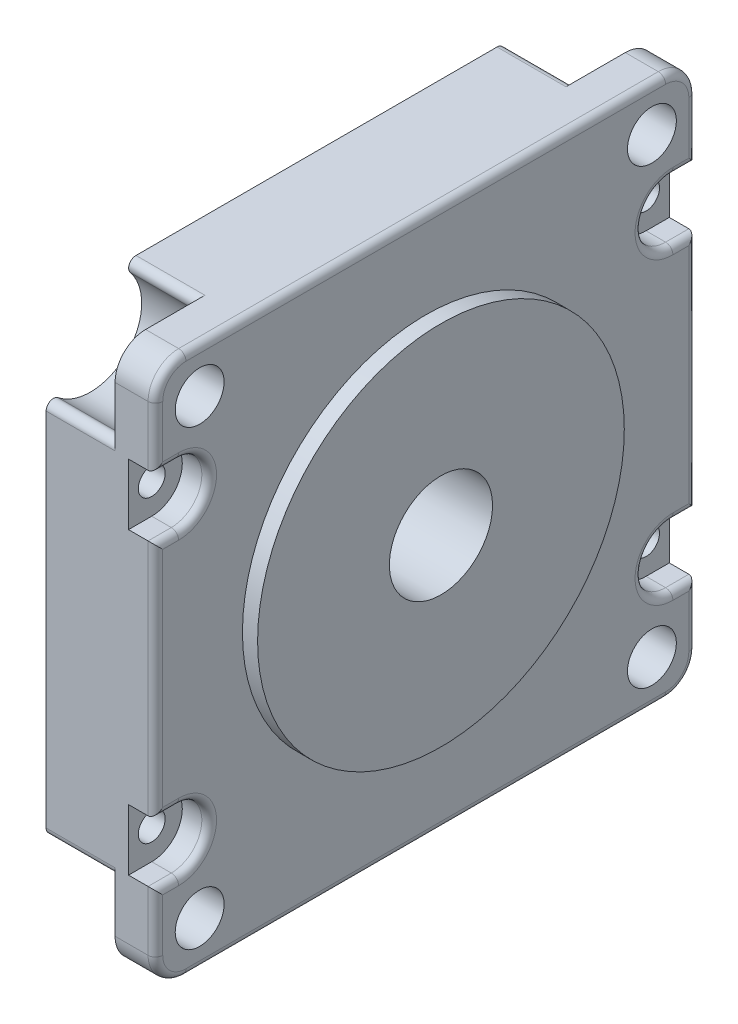
SolidWorks part; units mm, degrees
material "6061-T6 (SS)"
ref_plane "Front Plane" through (0, 0, 0) normal (0, 0, 1) x (1, 0, 0)
ref_plane "Top Plane" through (0, 0, 0) normal (0, 1, 0) x (1, 0, 0)
ref_plane "Right Plane" through (0, 0, 0) normal (1, 0, 0) x (0, 0, -1)
sketch "Sketch1" plane through (0, 0, 0) normal (1, 0, 0) x (0, 0, -1)
  line L1 (-28.0924, -28.0924) -> (28.0924, -28.0924)
  line L2 (-28.0924, -28.0924) -> (-28.0924, 28.0924)
  line L3 (-28.0924, 28.0924) -> (28.0924, 28.0924)
  line L4 (28.0924, -28.0924) -> (28.0924, 28.0924)
  line L5 (-28.0924, -28.0924) -> (28.0924, 28.0924) construction
  line L6 (-28.0924, 28.0924) -> (28.0924, -28.0924) construction
  point P0 (0, 0)
  dimension "D1" = 56.1848
  dimension "D2" = 56.1848
extrude "Boss-Extrude1" add sketch "Sketch1" along normal blind 11.3538
sketch "Sketch2" plane through (11.3538, 0, 0) normal (1, 0, 0) x (0, 0, -1)
  line L0 (0, 28.0924) -> (0, 0) construction
  line L1 (28.0924, 28.0924) -> (-28.0924, 28.0924) construction
  line L2 (0, 0) -> (-28.0924, 0) construction
  line L3 (-28.0924, 28.0924) -> (-28.0924, -28.0924) construction
  circle A0 centre (-23.495, 23.495) radius 2.54
  circle A1 centre (23.495, 23.495) radius 2.54
  circle A2 centre (23.495, -23.495) radius 2.54
  circle A3 centre (-23.495, -23.495) radius 2.54
  dimension "D1" = 5.08
  dimension "D2" = 46.99
  dimension "D3" = 46.99
extrude "Cut-Extrude1" cut sketch "Sketch2" against normal through all
sketch "Sketch3" plane through (11.3538, 0, 0) normal (1, 0, 0) x (0, 0, -1)
  line L0 (0, 28.0924) -> (0, 0) construction
  line L1 (28.0924, 28.0924) -> (-28.0924, 28.0924) construction
  line L2 (0, 0) -> (-28.0924, 0) construction
  line L3 (-28.0924, 28.0924) -> (-28.0924, -28.0924) construction
  line L4 (-25.6794, 15.5443) -> (-22.5044, 15.5443) construction
  line L5 (-22.5044, 15.5443) -> (-22.5044, 20.6548) construction
  line L6 (-25.6794, 18.7193) -> (-28.0924, 18.7193)
  line L7 (-25.6794, 12.3693) -> (-28.0924, 12.3693)
  line L8 (-28.0924, 18.7193) -> (-28.0924, 12.3693)
  line L9 (-28.0924, -18.7193) -> (-28.0924, -12.3693)
  line L10 (28.0924, 18.7193) -> (28.0924, 12.3693)
  line L11 (25.6794, 12.3693) -> (28.0924, 12.3693)
  line L12 (25.6794, 18.7193) -> (28.0924, 18.7193)
  line L13 (-25.6794, -12.3693) -> (-28.0924, -12.3693)
  line L14 (-25.6794, -18.7193) -> (-28.0924, -18.7193)
  line L15 (25.6794, -18.7193) -> (28.0924, -18.7193)
  line L16 (25.6794, -12.3693) -> (28.0924, -12.3693)
  line L17 (28.0924, -18.7193) -> (28.0924, -12.3693)
  arc A0 (-25.6794, 12.3693) -> (-25.6794, 18.7193) centre (-25.6794, 15.5443) ccw
  arc A1 (25.6794, 12.3693) -> (25.6794, 18.7193) centre (25.6794, 15.5443) cw
  arc A2 (-25.6794, -12.3693) -> (-25.6794, -18.7193) centre (-25.6794, -15.5443) cw
  arc A3 (25.6794, -12.3693) -> (25.6794, -18.7193) centre (25.6794, -15.5443) ccw
  dimension "D2" = 3.175
  dimension "D1" = 5.588
extrude "Cut-Extrude2" cut sketch "Sketch3" against normal blind 2.794
sketch "Sketch4" plane through (8.5598, 0, 0) normal (1, 0, 0) x (0, 0, -1)
  line L0 (0, 0) -> (0, 29.8799) construction
  line L1 (0, 0) -> (-28.2475, 0) construction
  circle A0 centre (-25.6794, 15.5443) radius 1.397
  circle A1 centre (25.6794, 15.5443) radius 1.397
  circle A2 centre (25.6794, -15.5443) radius 1.397
  circle A3 centre (-25.6794, -15.5443) radius 1.397
  dimension "D1" = 2.794
extrude "Cut-Extrude3" cut sketch "Sketch4" against normal through all
fillet "Fillet1" radius 3.175 4 edges at (5.6769, -28.0924, 28.0924) (5.6769, -28.0924, -28.0924) (5.6769, 28.0924, -28.0924) (5.6769, 28.0924, 28.0924)
sketch "Sketch5" plane through (11.3538, 0, 0) normal (1, 0, 0) x (0, 0, -1)
  circle A0 centre (0, 0) radius 19.05
  dimension "D1" = 38.1
extrude "Boss-Extrude2" add sketch "Sketch5" along normal blind 1.5748
sketch "Sketch6" plane through (12.9286, 0, 0) normal (1, 0, 0) x (0, 0, -1)
  circle A0 centre (0, 0) radius 5.3594
  dimension "D1" = 10.7188
extrude "Cut-Extrude4" cut sketch "Sketch6" against normal through all
fillet "Fillet3" radius 0.762 24 edges at (11.3538, 18.7193, -26.8859) (11.3538, 15.5443, -22.5044) (11.3538, -12.3693, -26.8859) (11.3538, -15.5443, -22.5044) (11.3538, -21.8183, -28.0924) (11.3538, -27.1625, -27.1625) (11.3538, -28.0924, 0) (11.3538, -27.1625, 27.1625) (11.3538, -18.7193, 26.8859) (11.3538, -15.5443, 22.5044) (11.3538, 12.3693, 26.8859) (11.3538, 15.5443, 22.5044) (11.3538, 21.8183, -28.0924) (11.3538, 27.1625, -27.1625) (11.3538, 28.0924, 0) (11.3538, 27.1625, 27.1625) (11.3538, 12.3693, -26.8859) (11.3538, 0, -28.0924) (11.3538, -18.7193, -26.8859) (11.3538, -21.8183, 28.0924) (11.3538, -12.3693, 26.8859) (11.3538, 0, 28.0924) (11.3538, 18.7193, 26.8859) (11.3538, 21.8183, 28.0924)
sketch "Sketch7" plane through (0, 0, 0) normal (-1, 0, 0) x (0, 0, 1)
  circle A0 centre (-23.495, 23.495) radius 5.334
  circle A1 centre (23.495, 23.495) radius 5.334
  circle A2 centre (23.495, -23.495) radius 5.334
  circle A3 centre (-23.495, -23.495) radius 5.334
  dimension "D1" = 10.668
extrude "Cut-Extrude5" cut sketch "Sketch7" against normal blind 7.1628
fillet "Fillet4" radius 0.762 8 edges at (3.5814, 20.7903, 28.0924) (3.5814, -20.7903, 28.0924) (3.5814, -28.0924, 20.7903) (3.5814, -28.0924, -20.7903) (3.5814, -20.7903, -28.0924) (3.5814, 28.0924, -20.7903) (3.5814, 28.0924, 20.7903) (3.5814, 20.7903, -28.0924)
